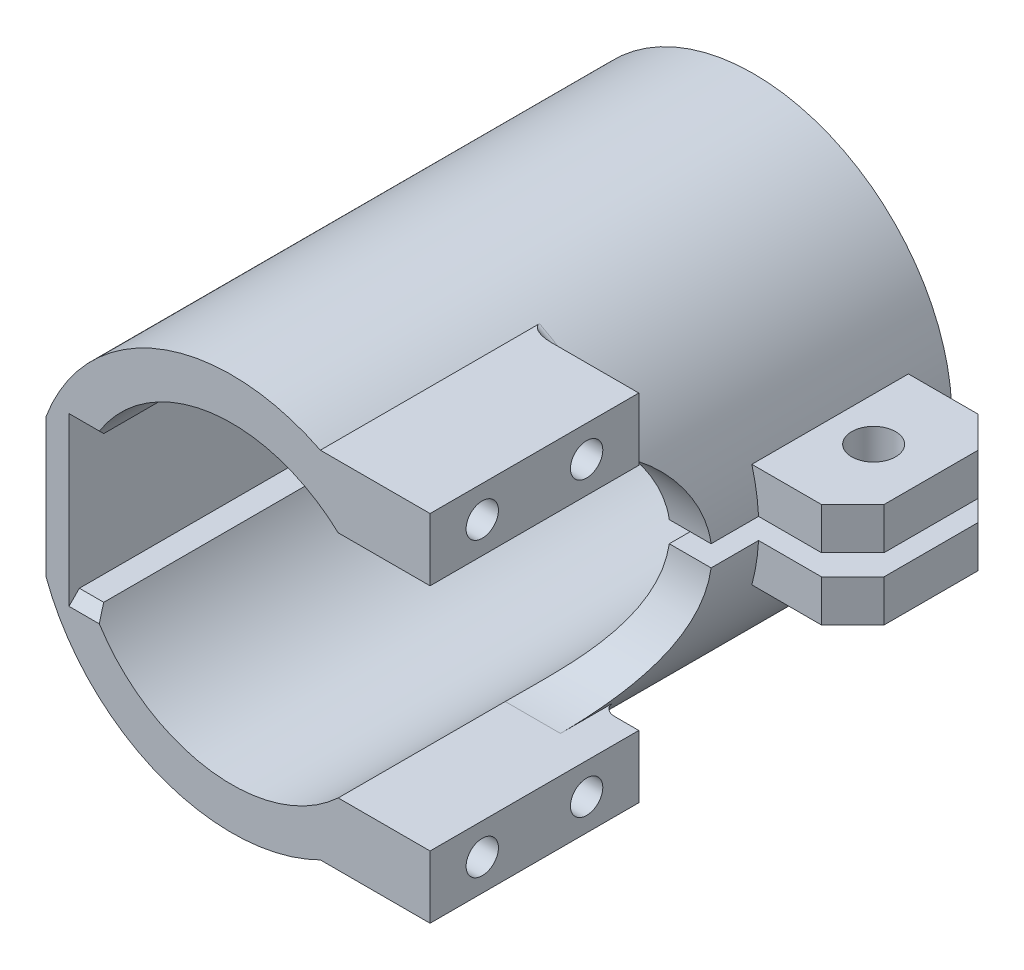
SolidWorks part; units mm, degrees
material "ABS"
ref_plane "前基準面" through (0, 0, 0) normal (0, 0, 1) x (1, 0, 0)
ref_plane "上基準面" through (0, 0, 0) normal (0, 1, 0) x (1, 0, 0)
ref_plane "右基準面" through (0, 0, 0) normal (1, 0, 0) x (0, 0, -1)
sketch "草圖1" plane through (0, 0, 0) normal (0, 0, 1) x (1, 0, 0)
  circle A1 centre (0, 0) radius 19
  dimension "D1" = 38
extrude "填料-伸長2" add sketch "草圖1" along normal blind 55
ref_plane "平面2" through (19, 0, 0) normal (1, 0, 0) x (0, 0, -1)
ref_plane "平面1" through (-19, 0, 0) normal (-1, 0, 0) x (0, 0, 1)
ref_plane "平面3" through (19, 0, 0) normal (1, 0, 0) x (0, 0, -1)
sketch "草圖11" plane through (0, 0, 55) normal (0, 0, 1) x (1, 0, 0)
  line L0 (0, 0) -> (-15.6, 0) construction
  line L2 (-15.6, 7) -> (-10.6, 7)
  line L3 (-15.6, 7) -> (-15.6, -7)
  line L4 (-15.6, -7) -> (-10.6, -7)
  line L5 (-10.6, 7) -> (-10.6, -7)
  dimension "D1" = 14
  dimension "D2" = 5
  dimension "D3" = 15.6
extrude "除料-伸長10" cut sketch "草圖11" against normal blind 40
ref_plane "平面4" through (19, 0, 0) normal (1, 0, 0) x (0, 0, -1)
sketch "草圖12" plane through (19, 0, 0) normal (1, 0, 0) x (0, 0, -1)
  line L0 (0, 0) -> (-55, 0) construction
  line L1 (-55, 7) -> (-55, -7) construction
  line L2 (0, -19) -> (0, 19) construction
  line L3 (-8.5, -5) -> (-23.5, -5)
  line L4 (-8.5, -5) -> (-8.5, 5)
  line L5 (-8.5, 5) -> (-23.5, 5)
  line L6 (-23.5, -5) -> (-23.5, 5)
  line L7 (-8.5, -5) -> (-23.5, 5) construction
  line L8 (-8.5, 5) -> (-23.5, -5) construction
  point P5 (-16, 0)
  dimension "D1" = 15
  dimension "D2" = 10
  dimension "D3" = 16
extrude "填料-伸長4" add sketch "草圖12" along normal blind 9 and the other way blind 2
sketch "草圖13" plane through (0, -5, 0) normal (0, -1, 0) x (1, 0, 0)
  line L0 (28, 16) -> (22.5, 16) construction
  line L1 (28, 23.5) -> (28, 8.5) construction
  circle A0 centre (22.5, 16) radius 2.1
  dimension "D1" = 4.2
  dimension "D2" = 5.5
extrude "除料-伸長11" cut sketch "草圖13" against normal through all
sketch "草圖14" plane through (0, 0, 23.5) normal (0, 0, 1) x (1, 0, 0)
  line L0 (28, 5) -> (18.3303, -5) construction
  line L2 (33.1652, -1) -> (13.1652, -1)
  line L3 (33.1652, -1) -> (33.1652, 1)
  line L4 (33.1652, 1) -> (13.1652, 1)
  line L5 (13.1652, -1) -> (13.1652, 1)
  line L6 (33.1652, -1) -> (13.1652, 1) construction
  line L7 (33.1652, 1) -> (13.1652, -1) construction
  point P2 (23.1652, 0)
  dimension "D1" = 20
  dimension "D2" = 2
sketch "草圖19" plane through (0, 0, 0) normal (0, 0, -1) x (-1, 0, 0)
  circle A0 centre (0, 0) radius 19
  dimension "D1" = 38
extrude "除料-伸長17" cut sketch "草圖19" against normal blind 5
sketch "草圖22" plane through (0, 0, 5) normal (0, 0, -1) x (-1, 0, 0)
  line L0 (17.8, 6.6453) -> (17.8, -6.6453)
  arc A0 (17.8, -6.6453) -> (17.8, 6.6453) centre (0, 0) ccw
  dimension "D1" = 38
  dimension "D2" = 17.8
extrude "除料-伸長19" cut sketch "草圖22" against normal through all
extrude "除料-伸長20" cut sketch "草圖14" against normal through all both and the other way through all
sketch "草圖23" plane through (19, 0, 0) normal (1, 0, 0) x (0, 0, -1)
  line L0 (-39, 11) -> (-55, 11)
  line L1 (-39, -11) -> (-55, -11)
  line L2 (-55, -11) -> (-55, 11)
  line L3 (-55, 19) -> (-55, 1) construction
  line L4 (-55, 7) -> (-55, -7) construction
  arc A0 (-39, -11) -> (-39, 11) centre (-39, 0) ccw
  point P1 (-39, -4.7508)
  point P6 (-54.2917, 5.2943)
  point P9 (-39, 0)
  point P10 (0, 0)
  point P13 (-55, 0)
  dimension "D1" = 16
  dimension "D2" = 22
extrude "除料-伸長21" cut sketch "草圖23" against normal blind 10
sketch "草圖24" plane through (19, 0, 0) normal (1, 0, 0) x (0, 0, -1)
  line L0 (-55, 11) -> (-35, 11)
  line L1 (-35, 11) -> (-35, 17)
  line L2 (-35, 17) -> (-55, 17)
  line L3 (-55, 19) -> (-55, 6.6453) construction
  line L4 (-55, 17) -> (-55, 11)
  point P4 (0, 0)
  dimension "D1" = 6
  dimension "D2" = 20
extrude "填料-伸長5" add sketch "草圖24" against normal blind 20
sketch "草圖3" plane through (0, 0, 55) normal (0, 0, 1) x (1, 0, 0)
  circle A0 centre (0, 0) radius 15
  dimension "D1" = 30
extrude "除料-伸長1" cut sketch "草圖3" against normal through all
chamfer "導角2" distance 3 angle 45 4 edges at (28, 3, 8.5) (28, -3, 8.5) (28, -3, 23.5) (28, 3, 23.5)
chamfer "導角3" distance 1 angle 45 2 edges at (-14.4332, -7, 55) (-14.4332, 7, 55)
fillet "圓角2" radius 1 1 edges at (12.3583, 14.4317, 35)
sketch "草圖25" plane through (19, 0, 0) normal (1, 0, 0) x (0, 0, -1)
  line L0 (-55, 14) -> (-50, 14) construction
  line L1 (-55, 17) -> (-55, 11) construction
  circle A0 centre (-50, 14) radius 1.55
  dimension "D1" = 3.1
  dimension "D2" = 5
extrude "除料-伸長22" cut sketch "草圖25" against normal blind 8
pattern_linear "直線複製排列1" count 2 spacing 10 along (0, 0, -1) of "除料-伸長22"
mirror "鏡射2" about plane through (0, 0, 0) normal (0, 1, 0) of "填料-伸長5", "除料-伸長1", "直線複製排列1", "圓角2"
